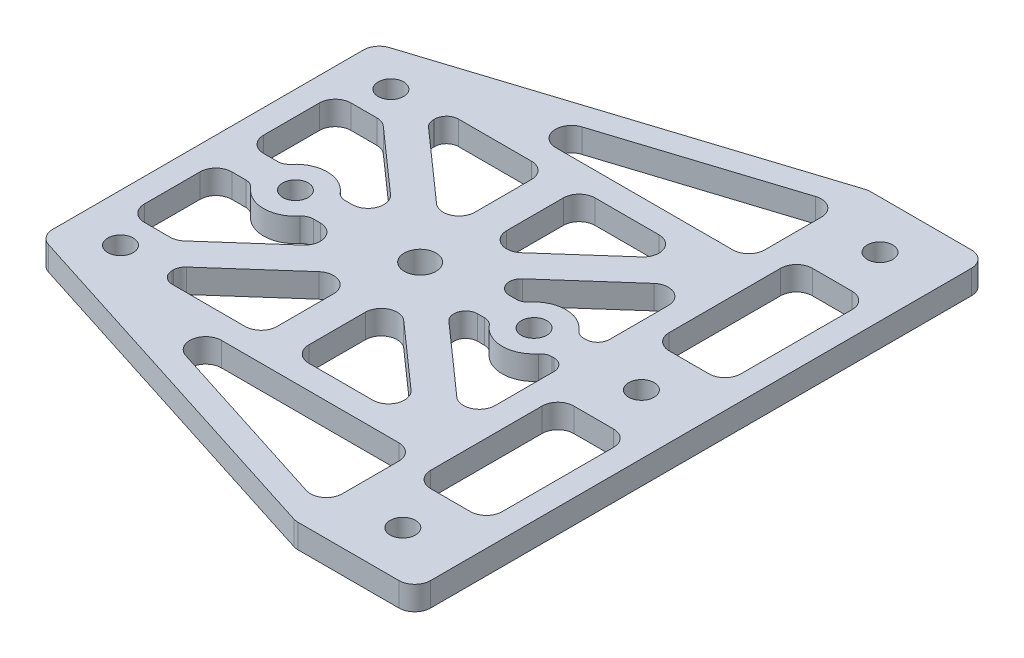
SolidWorks part; units mm, degrees
material "Thornel Mat VMA"
ref_plane "前视基准面" through (0, 0, 0) normal (0, 0, 1) x (1, 0, 0)
ref_plane "上视基准面" through (0, 0, 0) normal (0, 1, 0) x (1, 0, 0)
ref_plane "右视基准面" through (0, 0, 0) normal (1, 0, 0) x (0, 0, -1)
other "Configuration Table"
sketch "草图1" plane through (0, 0, 0) normal (0, 1, 0) x (1, 0, 0)
  line L0 (-15, 19.7671) -> (-15, -49.3288) construction
  line L1 (-30, 45) -> (-15, 45)
  line L2 (-30, 45) -> (-30, -45) construction
  line L3 (-30, -45) -> (-15, -45)
  line L4 (-15, 45) -> (-15, -45)
  line L5 (-115, 21) -> (-41, 21) construction
  line L6 (-115, 21) -> (-115, -21)
  line L7 (-115, -21) -> (-41, -21) construction
  line L8 (-41, 21) -> (-41, -21) construction
  line L9 (0, 0) -> (-115, 0) construction
  line L10 (-115, 21) -> (-30, 45)
  line L11 (-115, -21) -> (-30, -45)
  line L12 (-96.5993, 21) -> (-30, 39.8045)
  line L13 (-30, 39.8045) -> (-30, 21)
  line L14 (-30, 21) -> (-96.5993, 21)
  line L15 (-30, -21) -> (-96.5993, -21)
  line L16 (-96.5993, -21) -> (-30, -39.8045)
  line L17 (-30, -39.8045) -> (-30, -21)
  line L18 (-22.5, 45) -> (-22.5, -45) construction
  line L19 (-71, 21) -> (-71, -21) construction
  line L20 (-115, 21) -> (-96.5993, 21)
  line L21 (-115, -21) -> (-96.5993, -21)
  line L22 (-30, -39.8045) -> (-30, -45)
  line L23 (-30, 39.8045) -> (-30, 45)
  circle A0 centre (-22.5, 0) radius 1.6
  circle A1 centre (-22.5, -30) radius 1.6
  circle A2 centre (-22.5, 30) radius 1.6
  circle A3 centre (-71, 17) radius 1.6
  circle A4 centre (-71, -17) radius 1.6
  dimension "D9" = 3.2
  dimension "D10" = 3.2
  dimension "D11" = 3.2
  dimension "D14" = 3.2
  dimension "D15" = 3.2
  dimension "D1" = 26
  dimension "D2" = 74
  dimension "D3" = 15
  dimension "D4" = 15
  dimension "D5" = 15
  dimension "D6" = 42
  dimension "D7" = 90
  dimension "D8" = 5
  dimension "D12" = 15
  dimension "D13" = 15
  dimension "D16" = 17
  dimension "D17" = 17
  dimension "D18" = 30
extrude "凸台-拉伸1" add sketch "草图1" along normal blind 3 contours L23 L13 L14 L20 L6 L21 L15 L17 L22 L3 L4 L1 A4 A3 A2 A1 A0
sketch "草图2" plane through (0, 3, 0) normal (0, 1, 0) x (1, 0, 0)
  line L0 (-77, 21) -> (-77, -21)
  line L1 (-30, 21) -> (-115, 21) construction
  line L2 (-115, -21) -> (-30, -21) construction
  line L11 (-30, 45) -> (-30, 21)
  line L12 (-30, 21) -> (-115, 21)
  line L13 (-115, 21) -> (-115, -21)
  line L14 (-115, -21) -> (-30, -21)
  line L15 (-30, -21) -> (-30, -45)
  line L16 (-30, -45) -> (-15, -45)
  line L17 (-15, -45) -> (-15, 45)
  line L18 (-15, 45) -> (-30, 45)
  line L19 (-30, 45) -> (-30, 21)
  line L20 (-30, 21) -> (-115, 21)
  line L21 (-115, 21) -> (-115, -21)
  line L22 (-115, -21) -> (-30, -21)
  line L23 (-30, -21) -> (-30, -45)
  line L24 (-30, -45) -> (-15, -45)
  line L25 (-15, -45) -> (-15, 45)
  line L26 (-15, 45) -> (-30, 45)
  circle A0 centre (-71, -17) radius 1.6 construction
  line M8 (-30, 21) -> (-115, 21)
  line M9 (-115, 21) -> (-115, -21)
  line M10 (-115, -21) -> (-30, -21)
  dimension "D1" = 6
  dimension "D2" = 0
extrude "切除-拉伸1" cut sketch "草图2" against normal through all contours L0 M8 M9 M10
sketch "草图3" plane through (0, 3, 0) normal (0, 1, 0) x (1, 0, 0)
  line L0 (-77, 0) -> (0, 0) construction
  line L1 (-74, 13) -> (-65, 13)
  line L2 (-74, 13) -> (-74, -13)
  line L3 (-74, -13) -> (-65, -13)
  line L4 (-65, 13) -> (-65, -13)
  line L5 (-65, 18) -> (-30, 18)
  line L6 (-65, 18) -> (-65, -18)
  line L7 (-65, -18) -> (-30, -18)
  line L8 (-30, 18) -> (-30, -18)
  line L9 (-77, 21) -> (-77, -21) construction
  line L10 (-30, 21) -> (-77, 21) construction
  line L11 (-30, -45) -> (-30, -21) construction
  line L12 (-65, 13) -> (-30, -18)
  line L13 (-65, -13) -> (-30, 18)
  line L14 (-68.0164, 13) -> (-31.3261, -19.4972)
  line L15 (-65.0049, -15.676) -> (-28.6739, 16.5028)
  line L16 (-65, 15.6717) -> (-28.6739, -16.5028)
  line L17 (-68.0164, -13) -> (-31.3261, 19.4972)
  line L18 (-63.6739, 14.4972) -> (-28.6739, -16.5028) construction
  line L19 (-66.3261, 11.5028) -> (-31.3261, -19.4972) construction
  line L20 (-66.3261, -11.5028) -> (-31.3261, 19.4972) construction
  line L21 (-63.6739, -14.4972) -> (-28.6739, 16.5028) construction
  circle A0 centre (-71, 17) radius 1.6 construction
  dimension "D4" = 4
  dimension "D1" = 3
  dimension "D2" = 3
  dimension "D3" = 6
  dimension "D5" = 2
  dimension "D6" = 2
extrude "切除-拉伸2" cut sketch "草图3" against normal through all contours L3 L17 L6 L14 L1 L2 | L6 L17 L14 | L16 L17 L5 L6 | L15 L16 L8 | L15 L6 L7 L14
sketch "草图4" plane through (0, 3, 0) normal (0, 1, 0) x (1, 0, 0)
  line L0 (0, 0) -> (-22.5, 0) construction
  line L1 (-15, 45) -> (-15, -45) construction
  line L2 (-27, 24) -> (-18, 24)
  line L3 (-27, 24) -> (-27, 6)
  line L4 (-27, 6) -> (-18, 6)
  line L5 (-18, 24) -> (-18, 6)
  line L6 (-30, 45) -> (-15, 45)
  line L7 (-30, 45) -> (-30, 36)
  line L8 (-30, 36) -> (-15, 36)
  line L9 (-15, 45) -> (-15, 36)
  line L10 (-30, 21) -> (-30, 45) construction
  line L11 (-15, -45) -> (-15, -36)
  line L12 (-30, -36) -> (-15, -36)
  line L13 (-30, -45) -> (-30, -36)
  line L14 (-30, -45) -> (-15, -45)
  line L15 (-18, -24) -> (-18, -6)
  line L16 (-27, -6) -> (-18, -6)
  line L17 (-27, -24) -> (-27, -6)
  line L18 (-27, -24) -> (-18, -24)
  circle A0 centre (-22.5, 30) radius 1.6 construction
  circle A1 centre (-22.5, 0) radius 1.6 construction
  dimension "D1" = 6
  dimension "D2" = 6
  dimension "D3" = 6
  dimension "D4" = 3
  dimension "D5" = 3
extrude "切除-拉伸3" cut sketch "草图4" against normal through all
sketch "草图5" plane through (0, 3, 0) normal (0, 1, 0) x (1, 0, 0)
  line L0 (-30, 0) -> (-74, 0) construction
  line L1 (-30, 15.3283) -> (-30, -15.3283) construction
  line L2 (-74, 13) -> (-74, -13) construction
  line L3 (-30, 2) -> (-74, 2)
  line L4 (-30, -2) -> (-74, -2)
  line L5 (-74, 2) -> (-74, -2)
  line L6 (-30, 2) -> (-30, -2)
  dimension "D1" = 2
  dimension "D2" = 2
extrude "凸台-拉伸2" add sketch "草图5" against normal blind 3
sketch "草图6" plane through (0, 3, 0) normal (0, 1, 0) x (1, 0, 0)
  line L0 (-50.3226, 2.6717) -> (-50.3226, 18) construction
  line L1 (-65, 18) -> (-33.0164, 18) construction
  line L2 (-50.3226, -2.6717) -> (-50.3226, -18) construction
  line L3 (-65, -18) -> (-33.0164, -18) construction
  line L4 (-52.3226, -2.6717) -> (-52.3226, -18)
  line L5 (-48.3226, 2.6717) -> (-48.3226, 18)
  line L6 (-48.3226, -2.6717) -> (-48.3226, -18)
  line L7 (-52.3226, 2.6717) -> (-52.3226, 18)
  line L8 (-52.3226, 18) -> (-48.3226, 18)
  line L9 (-52.3226, 2.6717) -> (-48.3226, 2.6717)
  line L10 (-52.3226, -2.6717) -> (-48.3226, -2.6717)
  line L11 (-52.3226, -18) -> (-48.3226, -18)
  dimension "D1" = 2
  dimension "D2" = 2
extrude "凸台-拉伸3" add sketch "草图6" against normal blind 3
sketch "草图7" plane through (0, 3, 0) normal (0, 1, 0) x (1, 0, 0)
  line L0 (-77, 0) -> (-22.5, 0) construction
  line L1 (-77, 21) -> (-77, -21) construction
  line L2 (-52.3226, -18) -> (-48.3226, -18) construction
  line L3 (-50.3226, -18) -> (-50.3226, 0) construction
  circle A0 centre (-50.3226, 0) radius 2
  dimension "D1" = 4
extrude "切除-拉伸4" cut sketch "草图7" against normal through all
sketch "草图8" plane through (0, 3, 0) normal (0, 1, 0) x (1, 0, 0)
  line L0 (-77, 21) -> (-30, 36)
  line L1 (-30, 36) -> (-30, 32.8509)
  line L2 (-30, 21) -> (-30, 36) construction
  line L3 (-30, 32.8509) -> (-67.1329, 21)
  line L4 (-30, 21) -> (-77, 21) construction
  line L5 (-67.1329, 21) -> (-77, 21)
  line L6 (0, 0) -> (-15, 0) construction
  line L7 (-15, 36) -> (-15, -36) construction
  line L8 (-67.1329, -21) -> (-77, -21)
  line L9 (-30, -32.8509) -> (-67.1329, -21)
  line L10 (-30, -36) -> (-30, -32.8509)
  line L11 (-77, -21) -> (-30, -36)
  dimension "D1" = 3
extrude "凸台-拉伸4" add sketch "草图8" against normal blind 3
fillet "圆角2" radius 2 40 edges at (-77, 1.5, 21) (-30, 1.5, 36) (-15, 1.5, 36) (-30, 1.5, -36) (-77, 1.5, -21) (-15, 1.5, -36) (-30, 1.5, -21) (-67.1329, 1.5, -21) (-30, 1.5, -32.8509) (-30, 1.5, 32.8509) (-67.1329, 1.5, 21) (-30, 1.5, 21) (-52.3226, 1.5, -4.4431) (-52.3226, 1.5, -18) (-52.3226, 1.5, 18) (-52.3226, 1.5, 4.4431) (-33.0164, 1.5, 18) (-48.3226, 1.5, 18) (-48.3226, 1.5, 4.4431) (-33.0164, 1.5, -18) (-48.3226, 1.5, -4.4431) (-48.3226, 1.5, -18) (-18, 1.5, 6) (-18, 1.5, 24) (-27, 1.5, 24) (-27, 1.5, 6) (-18, 1.5, -24) (-18, 1.5, -6) (-27, 1.5, -6) (-27, 1.5, -24) (-30, 1.5, -15.3283) (-30, 1.5, 15.3283) (-55.5971, 1.5, 2) (-68.0164, 1.5, 13) (-74, 1.5, 13) (-74, 1.5, 2) (-74, 1.5, -2) (-68.0164, 1.5, -13) (-55.5971, 1.5, -2) (-74, 1.5, -13)
fillet "圆角1" radius 1.5 4 edges at (-65, 1.5, -18) (-65, 1.5, -15.6717) (-65, 1.5, 15.6717) (-65, 1.5, 18)
sketch "草图9" plane through (0, 3, 0) normal (0, 1, 0) x (1, 0, 0)
  line L0 (-50.3226, 0) -> (-36, 0) construction
  line L1 (-50.3226, 0) -> (-66, 0) construction
  circle A0 centre (-36, 0) radius 1.6
  circle A1 centre (-66, 0) radius 1.6
  circle A2 centre (-71, 17) radius 1.6 construction
  dimension "D3" = 3.2
  dimension "D4" = 3.2
  dimension "D1" = 5
  dimension "D2" = 35
extrude "切除-拉伸5" cut sketch "草图9" against normal through all
sketch "草图10" plane through (0, 3, 0) normal (0, 1, 0) x (1, 0, 0)
  circle A0 centre (-66, 0) radius 4
  circle A1 centre (-36, 0) radius 4
  circle A2 centre (-36, 0) radius 1.6 construction
  circle A3 centre (-66, 0) radius 1.6 construction
  circle A4 centre (-36, 0) radius 1.6
  circle A5 centre (-66, 0) radius 1.6
  dimension "D1" = 8
  dimension "D2" = 8
extrude "凸台-拉伸5" add sketch "草图10" against normal blind 3
fillet "圆角3" radius 1.5 12 edges at (-39.4641, 1.5, -2) (-32.5359, 1.5, -2) (-32.5359, 1.5, 2) (-39.4641, 1.5, 2) (-62.5359, 1.5, 2) (-69.4641, 1.5, 2) (-69.4641, 1.5, -2) (-62.5359, 1.5, -2) (-30, 1.5, 2) (-45.0481, 1.5, 2) (-30, 1.5, -2) (-45.0481, 1.5, -2)
